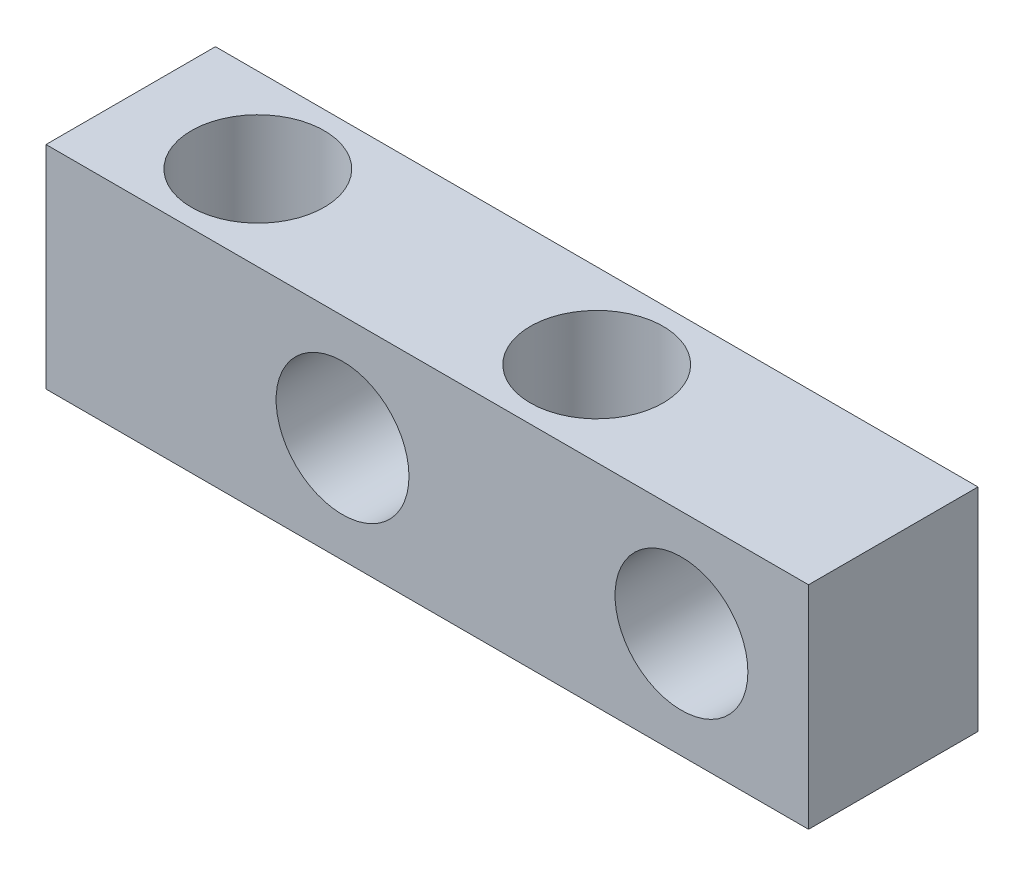
SolidWorks part; units mm, degrees
ref_plane "Front Plane" through (0, 0, 0) normal (0, 0, 1) x (1, 0, 0)
ref_plane "Top Plane" through (0, 0, 0) normal (0, 1, 0) x (1, 0, 0)
ref_plane "Right Plane" through (0, 0, 0) normal (1, 0, 0) x (0, 0, -1)
sketch "Sketch1" plane through (0, 0, 0) normal (0, 0, 1) x (1, 0, 0)
  line L0 (-3.175, 3.9688) -> (-3.175, -3.9688) construction
  line L1 (-14.2875, -3.9688) -> (14.2875, -3.9687)
  line L2 (-14.2875, -3.9688) -> (-14.2875, 3.9688)
  line L3 (-14.2875, 3.9688) -> (14.2875, 3.9687)
  line L4 (14.2875, -3.9687) -> (14.2875, 3.9687)
  line L5 (-14.2875, -3.9688) -> (14.2875, 3.9687) construction
  line L6 (-14.2875, 3.9688) -> (14.2875, -3.9687) construction
  circle A0 centre (-3.175, 0) radius 2.4892
  circle A1 centre (9.525, 0) radius 2.4892
  point P0 (0, 0)
  point P11 (-14.2875, 0)
  dimension "D2" = 4.9784
  dimension "D3" = 11.1125
  dimension "D1" = 7.9375
  dimension "1" = 28.575
  dimension "D4" = 12.7
extrude "Boss-Extrude1" add sketch "Sketch1" along normal mid plane 6.35
sketch "Sketch2" plane through (0, 0, 0) normal (0, 1, 0) x (1, 0, 0)
  line L0 (-14.2875, -3.175) -> (-14.2875, 3.175) construction
  line L1 (-6.35, -3.175) -> (0, -3.175) construction
  line L2 (14.2875, -3.175) -> (-14.2875, -3.175) construction
  line L6 (-5.6642, -3.175) -> (-0.6858, -3.175) construction
  circle A0 centre (3.175, 0) radius 2.4892
  circle A1 centre (-9.525, 0) radius 2.4892
  point P4 (-3.175, -3.175)
  point P5 (5.4805, 0)
  point P8 (-14.2875, 0)
  point P9 (-7.6523, 0)
  point P10 (-10.8167, 0)
  point P15 (-10.7859, 0)
  point P16 (2.3048, 0)
  point P19 (-8.4472, 0)
  dimension "D1" = 4.9784
  dimension "D2" = 6.35
  dimension "D3" = 6.35
  dimension "D4" = 6.35
extrude "Cut-Extrude1" cut sketch "Sketch2" against normal through all both and the other way through all
equation "\"D4@Sketch2\"=\"D3@Sketch2\""
